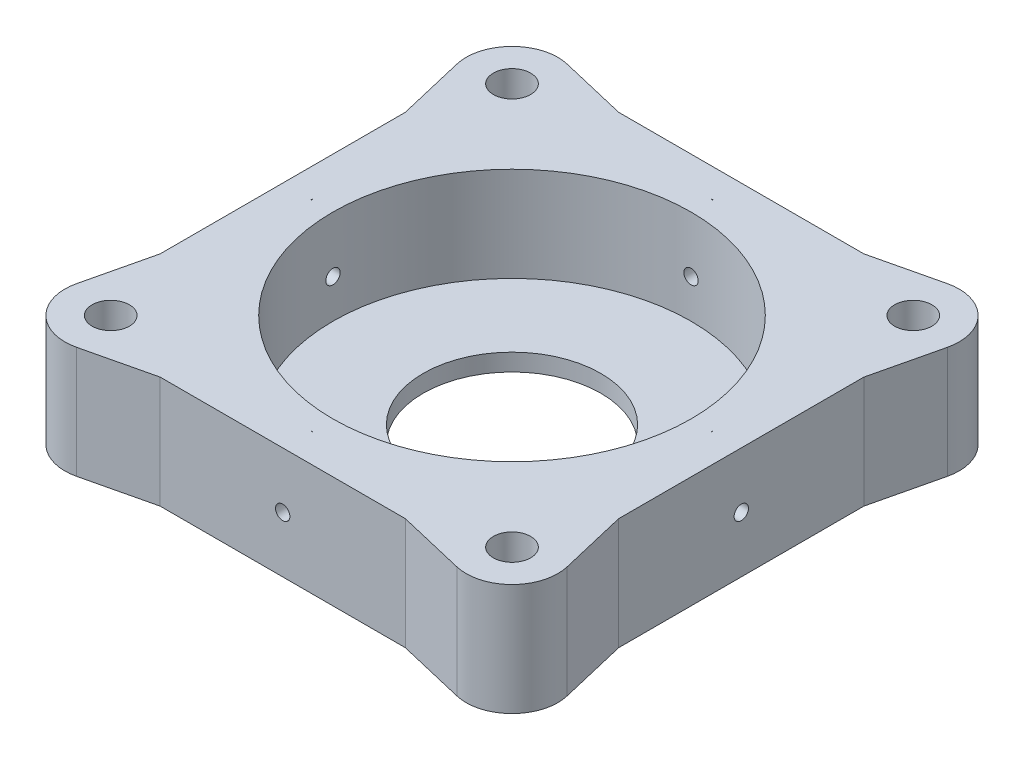
SolidWorks part; units mm, degrees
ref_plane "Front Plane" through (0, 0, 0) normal (0, 0, 1) x (1, 0, 0)
ref_plane "Top Plane" through (0, 0, 0) normal (0, 1, 0) x (1, 0, 0)
ref_plane "Right Plane" through (0, 0, 0) normal (1, 0, 0) x (0, 0, -1)
sketch "Sketch1" plane through (0, 0, 0) normal (0, 1, 0) x (1, 0, 0)
  line L0 (0, 35) -> (0, -35) construction
  line L1 (35, -35) -> (-35, -35)
  line L2 (35, -35) -> (35, 35)
  line L3 (35, 35) -> (-35, 35)
  line L4 (-35, -35) -> (-35, 35)
  line L5 (35, -35) -> (-35, 35) construction
  line L6 (35, 35) -> (-35, -35) construction
  line L7 (-35, 0) -> (35, 0) construction
  line L8 (-33.1578, 42.785) -> (7.8292, 33.0863)
  line L9 (-42.785, 33.1578) -> (-33.0863, -7.8292)
  line L10 (42.785, 33.1578) -> (33.0863, -7.8292)
  line L11 (33.1578, 42.785) -> (-7.8292, 33.0863)
  line L12 (-42.785, -33.1578) -> (-33.0863, 7.8292)
  line L13 (-33.1578, -42.785) -> (7.8292, -33.0863)
  line L14 (33.1578, -42.785) -> (-7.8292, -33.0863)
  line L15 (42.785, -33.1578) -> (33.0863, 7.8292)
  line L17 (40, -40) -> (-40, -40)
  line L18 (40, -40) -> (40, 40)
  line L19 (40, 40) -> (-40, 40)
  line L20 (-40, -40) -> (-40, 40)
  line L21 (40, -40) -> (-40, 40) construction
  line L22 (40, 40) -> (-40, -40) construction
  circle A0 centre (0, 0) radius 15.5
  circle A1 centre (0, 0) radius 34
  circle A2 centre (-35, 35) radius 3.25
  circle A3 centre (0, 0) radius 40
  circle A4 centre (-35, 35) radius 8
  circle A5 centre (35, 35) radius 3.25
  circle A6 centre (35, 35) radius 8
  circle A7 centre (-35, -35) radius 3.25
  circle A8 centre (-35, -35) radius 8
  circle A9 centre (35, -35) radius 3.25
  circle A10 centre (35, -35) radius 8
  point P41 (-39.0586, 39.0586)
  dimension "D1" = 31
  dimension "D2" = 68
  dimension "D3" = 6.5
  dimension "D5" = 80
  dimension "D4" = 16
  dimension "D6" = 70
extrude "Boss-Extrude1" add sketch "Sketch1" along normal blind 19.5 contours L19 A4 L20 | L3 A4 L19 L20 L4 A2 | L4 A4 L3 A2 | A4 L9 L20 | A4 L20 L9 A3 L4 | A3 L9 L20 | L4 A3 L9 | L9 A3 L12 L4 | A3 L20 L12 | L12 A3 L4 | L20 A8 L4 A3 L12 | L12 A8 L20 | A8 L17 L20 | A8 L20 L17 L1 A7 L4 | A8 L4 A7 L1 | L4 A8 L1 A3 | L4 A3 L1 L13 L14 A1 L9 L12 | L3 A3 L4 L9 L12 A1 L11 L8 | A1 L12 L9 | A4 L4 A3 L3 | A4 L3 A3 L8 L19 | A4 L19 L8 | A3 L19 L8 | L8 A3 L3 | L11 A3 L8 L3 | A1 L8 L11 | L3 A3 L11 | L2 A3 L3 L11 L8 A1 L15 L10 | L3 A6 L19 L11 A3 | A3 L11 L19 | L19 A6 L11 | L2 A6 L3 A3 | A6 L2 A5 L3 | A6 L3 A5 L2 L18 L19 | A6 L19 L18 | L10 A6 L18 | L18 A6 L2 A3 L10 | A3 L18 L10 | L10 A3 L2 | L15 A3 L10 L2 | A3 L15 L18 | L2 A3 L15 | A1 L10 L15 | L1 A3 L2 L15 L10 A1 L13 L14 | A10 L18 L15 A3 L2 | A10 L15 L18 | A10 L2 A3 L1 | L18 A10 L2 A9 L1 L17 | L2 A10 L1 A9 | A10 L18 L17 | A10 L17 L14 | A10 L1 A3 L14 L17 | L14 A3 L1 | A3 L17 L14 | A3 L14 L1 L13 | A1 L14 L13 | L1 A3 L13 | A3 L13 L17 | L1 A8 L17 L13 A3 | L17 A8 L13 | A1 A0
sketch "Sketch2" plane through (0, 19.5, 0) normal (0, 1, 0) x (1, 0, 0)
  circle A0 centre (0, 0) radius 31.25
  point P2 (0, 0)
  point P3 (-0.9597, 0)
  dimension "D1" = 62.5
extrude "Cut-Extrude1" cut sketch "Sketch2" against normal blind 16.5
sketch "Sketch3" plane through (0, 0, 0) normal (0, -1, 0) x (1, 0, 0)
  circle A0 centre (-35, 35) radius 5
  circle A1 centre (35, 35) radius 5
  circle A2 centre (35, -35) radius 5
  circle A3 centre (-35, -35) radius 5
  dimension "D1" = 10
extrude "Cut-Extrude2" cut sketch "Sketch3" against normal blind 6
sketch "Sketch4" plane through (0, 0, 40) normal (0, 0, 1) x (1, 0, 0)
  line L0 (0, 0) -> (0, 19.5) construction
  line L1 (21.3883, 0) -> (-21.3883, 0) construction
  line L2 (21.3883, 19.5) -> (-21.3883, 19.5) construction
  circle A0 centre (0, 9.75) radius 1.25
  dimension "D1" = 2.5
extrude "Cut-Extrude3" cut sketch "Sketch4" against normal up to surface (80 mm away) up to face at (0, 9.75, -40)
sketch "Sketch5" plane through (40, 0, 0) normal (1, 0, 0) x (0, 0, -1)
  line L0 (0, 0) -> (0, 19.5) construction
  line L1 (-21.3883, 19.5) -> (21.3883, 19.5) construction
  circle A0 centre (0, 9.75) radius 1.25
  dimension "D1" = 2.5
extrude "Cut-Extrude4" cut sketch "Sketch5" against normal up to surface (80 mm away) up to face at (-40, 9.75, 0)
